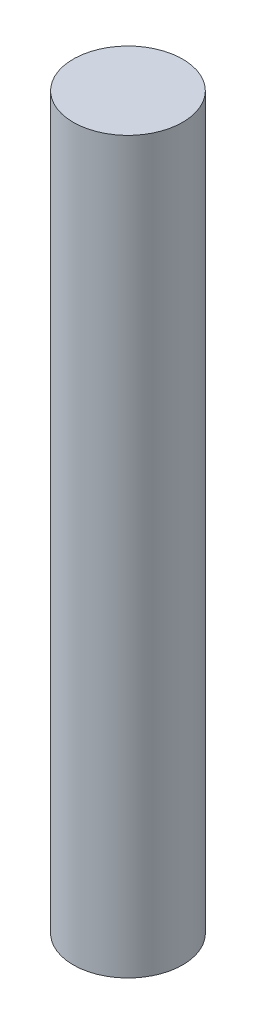
SolidWorks part; units mm, degrees
ref_plane "前基準面" through (0, 0, 0) normal (0, 0, 1) x (1, 0, 0)
ref_plane "上基準面" through (0, 0, 0) normal (0, 1, 0) x (1, 0, 0)
ref_plane "右基準面" through (0, 0, 0) normal (1, 0, 0) x (0, 0, -1)
sketch "草圖1" plane through (0, 0, 0) normal (0, 1, 0) x (1, 0, 0)
  circle A0 centre (0, 0) radius 1.5
  dimension "D1" = 3
extrude "填料-伸長1" add sketch "草圖1" along normal blind 20
